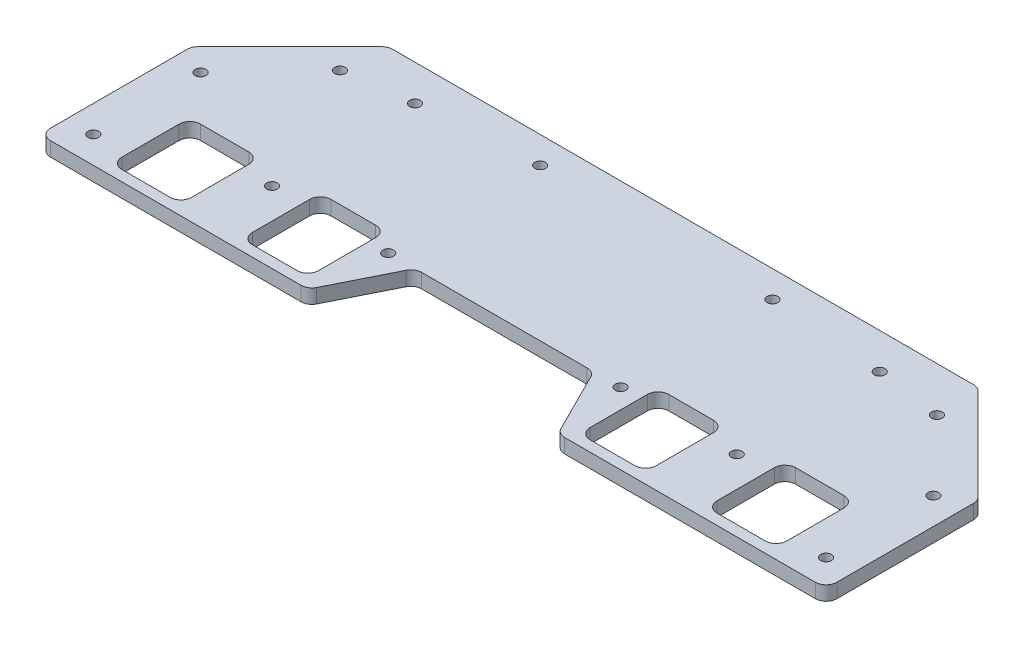
SolidWorks part; units mm, degrees
ref_plane "前视基准面" through (0, 0, 0) normal (0, 0, 1) x (1, 0, 0)
ref_plane "上视基准面" through (0, 0, 0) normal (0, 1, 0) x (1, 0, 0)
ref_plane "右视基准面" through (0, 0, 0) normal (1, 0, 0) x (0, 0, -1)
sketch "草图1" plane through (0, 0, 0) normal (0, 1, 0) x (1, 0, 0)
  line L1 (-137.5, -35) -> (-67.5, -35)
  line L2 (-137.5, -35) -> (-137.5, 15)
  line L3 (-117.5, 35) -> (72.5, 35)
  line L4 (92.5, -35) -> (92.5, 15)
  line L5 (22.5, -35) -> (92.5, -35)
  line L6 (-137.5, 15) -> (-117.5, 35)
  line L7 (-22.5, 61.4781) -> (-22.5, -135.1347) construction
  line L8 (92.5, 15) -> (72.5, 35)
  line L9 (-47.5, -15) -> (2.5, -15)
  line L10 (-67.5, -35) -> (-57.5, -35)
  line L11 (-57.5, -35) -> (-47.5, -15)
  line L12 (22.5, -35) -> (12.5, -35)
  line L14 (12.5, -35) -> (2.5, -15)
  point P0 (0, 0)
  point P6 (0, -35)
  dimension "D1" = 230
  dimension "D2" = 10
  dimension "D3" = 50
  dimension "D4" = 20
  dimension "D5" = 70
  dimension "D6" = 70
  dimension "D7" = 135
  dimension "D8" = 20
  dimension "D9" = 10
extrude "凸台-拉伸1" add sketch "草图1" along normal blind 4
sketch "草图2" plane through (0, 4, 0) normal (0, 1, 0) x (1, 0, 0)
  line L0 (-137.5, -35) -> (-57.5, -35) construction
  line L1 (-47.5, -15) -> (2.5, -15) construction
  line L2 (-22.5, 54.05) -> (-22.5, -68.4645) construction
  circle A0 centre (-87.5, -15) radius 1.5
  circle A1 centre (-87.5, 25) radius 1.5
  circle A2 centre (42.5, 25) radius 1.5
  circle A3 centre (42.5, -15) radius 1.5
  point P8 (-22.5, -15)
  dimension "D1" = 40
  dimension "D2" = 20
  dimension "D3" = 65
extrude "切除-拉伸1" cut sketch "草图2" against normal blind 4
sketch "草图3" plane through (0, 4, 0) normal (0, 1, 0) x (1, 0, 0)
  line L1 (-137.5, -35) -> (-127.5, -35)
  line L2 (-137.5, -35) -> (-137.5, 34.6789)
  line L3 (-137.5, 34.6789) -> (-127.5, 34.6789)
  line L4 (-127.5, -35) -> (-127.5, 34.6789)
  line L5 (92.5, -35) -> (82.5, -35)
  line L6 (92.5, -35) -> (92.5, 58.0477)
  line L7 (92.5, 58.0477) -> (82.5, 58.0477)
  line L8 (82.5, -35) -> (82.5, 58.0477)
  dimension "D1" = 10
  dimension "D2" = 10
extrude "切除-拉伸2" cut sketch "草图3" against normal blind 4
sketch "草图4" plane through (0, 4, 0) normal (0, 1, 0) x (1, 0, 0)
  line L0 (-127.5, 12.5) -> (-92.1971, 47.8029)
  line L1 (-127.5, -35) -> (-127.5, 25) construction
  line L2 (-92.1971, 47.8029) -> (-150.179, 47.8029)
  line L3 (-150.179, 47.8029) -> (-127.5, 12.5)
  line L4 (82.5, 12.5) -> (37.0053, 57.9947)
  line L5 (82.5, 25) -> (82.5, -35) construction
  line L6 (37.0053, 57.9947) -> (96.5441, 56.2052)
  line L7 (96.5441, 56.2052) -> (82.5, 12.5)
  line L8 (-127.5, -35) -> (-57.5, -35) construction
  line L9 (12.5, -35) -> (82.5, -35) construction
  dimension "D1" = 47.5
  dimension "D2" = 47.5
extrude "切除-拉伸3" cut sketch "草图4" against normal blind 4
sketch "草图5" plane through (0, 4, 0) normal (0, 1, 0) x (1, 0, 0)
  line L0 (-127.5, 12.5) -> (-132.5, 7.5)
  line L1 (-132.5, 7.5) -> (-132.5, -35)
  line L2 (-132.5, -35) -> (-127.5, -35)
  line L3 (-127.5, -35) -> (-127.5, 12.5)
  line L4 (-22.5, 45.9563) -> (-22.5, -39.7367) construction
  line L5 (82.5, -35) -> (82.5, 12.5)
  line L6 (87.5, -35) -> (82.5, -35)
  line L7 (87.5, 7.5) -> (87.5, -35)
  line L8 (82.5, 12.5) -> (87.5, 7.5)
  line L9 (-127.5, 12.5) -> (-105, 35) construction
  dimension "D1" = 5
extrude "凸台-拉伸2" add sketch "草图5" against normal up to surface (4 mm away) up to face at (-22.5, 0, 7.5)
sketch "草图6" plane through (0, 4, 0) normal (0, 1, 0) x (1, 0, 0)
  line L0 (12.5, -35) -> (87.5, -35) construction
  line L1 (-22.5, 44.5061) -> (-22.5, -48.9521) construction
  circle A0 centre (59.5, -29) radius 1.5
  circle A1 centre (42.5, -15) radius 1.5 construction
  circle A2 centre (59.5, -19) radius 1.5
  circle A3 centre (23.5, -19) radius 1.5
  circle A4 centre (23.5, -29) radius 1.5
  circle A5 centre (-68.5, -29) radius 1.5
  circle A6 centre (-68.5, -19) radius 1.5
  circle A7 centre (-104.5, -19) radius 1.5
  circle A8 centre (-104.5, -29) radius 1.5
  dimension "D1" = 17
  dimension "D2" = 6
  dimension "D3" = 10
  dimension "D4" = 2
extrude "切除-拉伸4" cut sketch "草图6" against normal blind 10
sketch "草图7" plane through (0, 4, 0) normal (0, 1, 0) x (1, 0, 0)
  line L0 (-132.5, -35) -> (-57.5, -35) construction
  line L1 (-115.5, -10) -> (-96, -10)
  line L2 (-115.5, -10) -> (-115.5, -32)
  line L3 (-115.5, -32) -> (-96, -32)
  line L4 (-96, -10) -> (-96, -32)
  line L5 (-79, -10) -> (-60.5, -10)
  line L6 (-79, -10) -> (-79, -32)
  line L7 (-79, -32) -> (-60.5, -32)
  line L8 (-60.5, -10) -> (-60.5, -32)
  line L9 (-22.5, 47.3103) -> (-22.5, -44.5027) construction
  line L10 (15.5, -10) -> (15.5, -32)
  line L11 (34, -32) -> (15.5, -32)
  line L12 (34, -10) -> (34, -32)
  line L13 (34, -10) -> (15.5, -10)
  line L14 (51, -10) -> (51, -32)
  line L15 (70.5, -32) -> (51, -32)
  line L16 (70.5, -10) -> (70.5, -32)
  line L17 (70.5, -10) -> (51, -10)
  circle A0 centre (-104.5, -29) radius 1.5 construction
  circle A1 centre (-68.5, -29) radius 1.5 construction
  dimension "D1" = 22
  dimension "D2" = 22
  dimension "D3" = 18.5
  dimension "D4" = 19.5
  dimension "D5" = 8.5
  dimension "D6" = 10.5
  dimension "D7" = 3
  dimension "D8" = 3
extrude "切除-拉伸5" cut sketch "草图7" against normal blind 10
fillet "圆角1" radius 3 8 edges at (-115.5, 2, 10) (-96, 2, 32) (-115.5, 2, 32) (-96, 2, 10) (-79, 2, 10) (-60.5, 2, 32) (-79, 2, 32) (-60.5, 2, 10)
fillet "圆角2" radius 3 8 edges at (34, 2, 32) (15.5, 2, 32) (15.5, 2, 10) (34, 2, 10) (70.5, 2, 32) (51, 2, 32) (51, 2, 10) (70.5, 2, 10)
fillet "圆角3" radius 3 10 edges at (60, 2, -35) (-105, 2, -35) (-132.5, 2, -7.5) (-132.5, 2, 35) (-57.5, 2, 35) (-47.5, 2, 15) (2.5, 2, 15) (12.5, 2, 35) (87.5, 2, 35) (87.5, 2, -7.5)
sketch "草图8" plane through (0, 0, 0) normal (0, -1, 0) x (1, 0, 0)
  line L0 (-132.5, -6.2574) -> (-132.5, 32) construction
  line L1 (-129.5, 35) -> (-59.3541, 35) construction
  line L2 (58.7574, -35) -> (-103.7574, -35) construction
  line L3 (-22.5, -47.9757) -> (-22.5, 45.6968) construction
  line L4 (-45.6459, 15) -> (0.6459, 15) construction
  circle A0 centre (-125, 27.5) radius 1.5
  circle A1 centre (-125, -2.5) radius 1.5
  circle A2 centre (-55, 15) radius 1.5
  circle A3 centre (-55, -27.5) radius 1.5
  circle A4 centre (10, -27.5) radius 1.5
  circle A5 centre (10, 15) radius 1.5
  circle A6 centre (80, -2.5) radius 1.5
  circle A7 centre (80, 27.5) radius 1.5
  circle A8 centre (-106, -22.5) radius 1.5
  circle A9 centre (61, -22.5) radius 1.5
  point P26 (-22.5, 15)
  dimension "D1" = 3
  dimension "D2" = 7.5
  dimension "D3" = 7.5
  dimension "D4" = 30
  dimension "D5" = 7.5
  dimension "D6" = 32.5
  dimension "D7" = 32.5
  dimension "D9" = 12.5
  dimension "D10" = 26.5
  dimension "D8" = 0
extrude "切除-拉伸6" cut sketch "草图8" against normal blind 10
